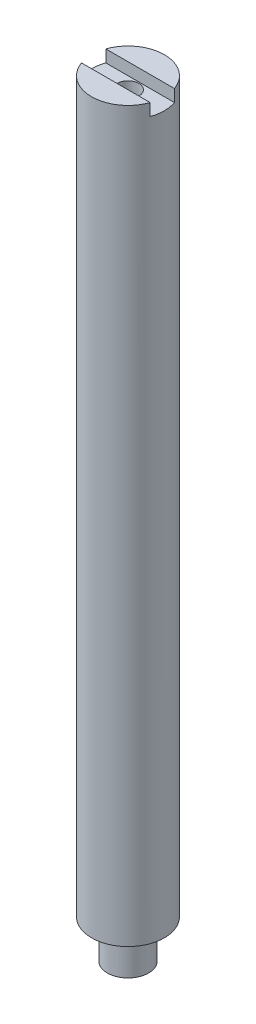
SolidWorks part; units mm, degrees
ref_plane "Front Plane" through (0, 0, 0) normal (0, 0, 1) x (1, 0, 0)
ref_plane "Top Plane" through (0, 0, 0) normal (0, 1, 0) x (1, 0, 0)
ref_plane "Right Plane" through (0, 0, 0) normal (1, 0, 0) x (0, 0, -1)
sketch "Sketch1" plane through (0, 0, 0) normal (0, 1, 0) x (1, 0, 0)
  circle A0 centre (0, 0) radius 4.25
  dimension "D1" = 8.5
extrude "Boss-Extrude1" add sketch "Sketch1" along normal blind 7.9
sketch "Sketch2" plane through (0, 7.9, 0) normal (0, 1, 0) x (1, 0, 0)
  circle A0 centre (0, 0) radius 7.5
  dimension "D1" = 15
extrude "Boss-Extrude2" add sketch "Sketch2" along normal blind 150 contours A0
sketch "Sketch3" plane through (0, 157.9, 0) normal (0, 1, 0) x (1, 0, 0)
  circle A0 centre (0, 0) radius 2.25
  dimension "D1" = 4.5
extrude "Cut-Extrude1" cut sketch "Sketch3" against normal through all
sketch "Sketch4" plane through (0, 157.9, 0) normal (0, 1, 0) x (1, 0, 0)
  line L1 (-7.5, -2.5) -> (7.5, -2.5)
  line L2 (-7.5, -2.5) -> (-7.5, 2.5)
  line L3 (-7.5, 2.5) -> (7.5, 2.5)
  line L4 (7.5, -2.5) -> (7.5, 2.5)
  line L5 (-7.5, -2.5) -> (7.5, 2.5) construction
  line L6 (-7.5, 2.5) -> (7.5, -2.5) construction
  circle A0 centre (0, 0) radius 7.5 construction
  point P0 (0, 0)
  point P5 (6.8647, -4.6561)
  point P6 (9.5509, 5.2928)
  dimension "D1" = 5
extrude "Cut-Extrude2" cut sketch "Sketch4" against normal blind 2.5
